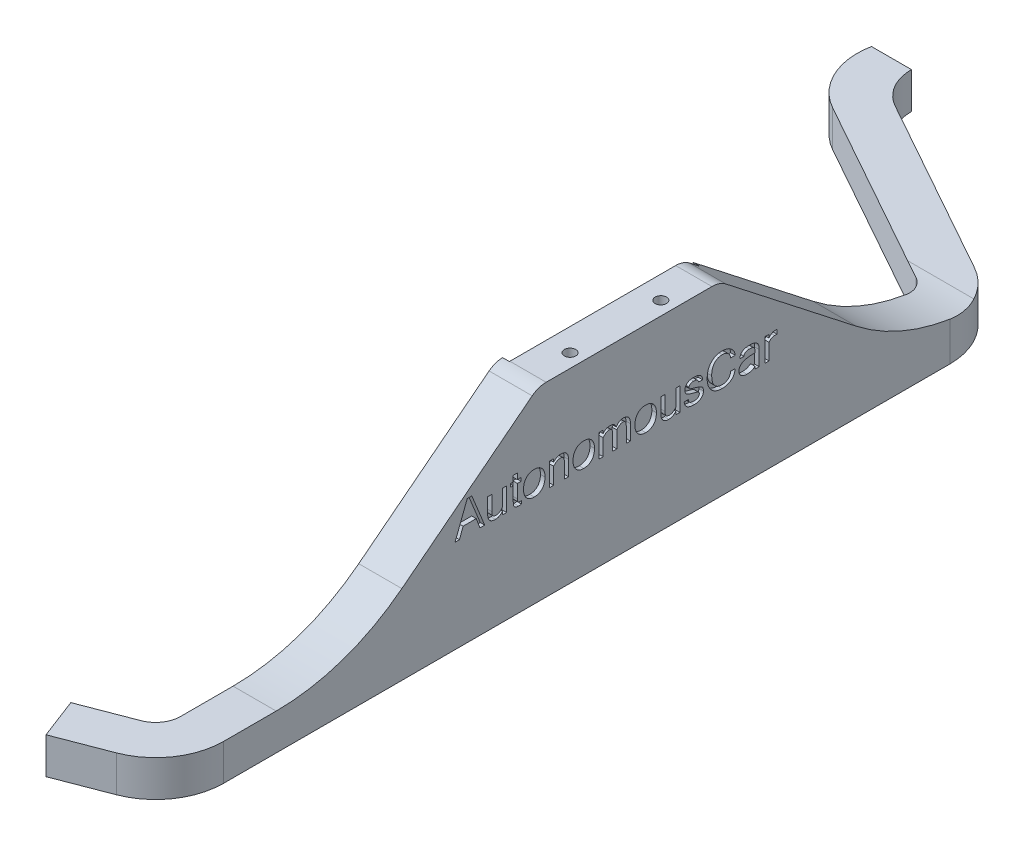
SolidWorks part; units mm, degrees
ref_plane "Plan de face" through (0, 0, 0) normal (0, 0, 1) x (1, 0, 0)
ref_plane "Plan de dessus" through (0, 0, 0) normal (0, 1, 0) x (1, 0, 0)
ref_plane "Plan de droite" through (0, 0, 0) normal (1, 0, 0) x (0, 0, -1)
sketch "Esquisse1" plane through (0, 0, 0) normal (0, 1, 0) x (1, 0, 0)
  line L0 (50.7636, -98.741) -> (61.9667, -94.4409)
  line L1 (65.5, -89.3) -> (65.5, 70.7)
  line L2 (62.6824, 75.5015) -> (21.1873, 98.6833)
  line L3 (54.1678, -107.6101) -> (50.7636, -98.741)
  line L4 (67.3157, 83.795) -> (27.7151, 105.9185)
  line L5 (75, -89.3) -> (75, 70.7)
  line L6 (13.7802, 114.6485) -> (22.5922, 114.6485)
  line L7 (54.1678, -107.6101) -> (65.3709, -103.31)
  line L8 (27.6229, 105.97) -> (67.3157, 83.795) construction
  line L9 (11.8444, -113.6793) -> (61.9667, -94.4409) construction
  line L10 (15.2486, -122.5484) -> (65.3709, -103.31) construction
  arc A0 (61.9667, -94.4409) -> (65.5, -89.3) centre (59.9934, -89.3) ccw
  arc A1 (65.5, 70.7) -> (62.6824, 75.5015) centre (60, 70.7) ccw
  arc A2 (21.1873, 98.6833) -> (13.7802, 114.6485) centre (28.503, 111.7784) cw
  arc A3 (75, 70.7) -> (67.3157, 83.795) centre (60, 70.7) ccw construction
  arc A4 (75, 70.7) -> (67.3157, 83.795) centre (60, 70.7) ccw
  arc A5 (65.3709, -103.31) -> (75, -89.3) centre (59.9934, -89.3) ccw
  arc A6 (65.3709, -103.31) -> (75, -89.3) centre (59.9934, -89.3) ccw construction
  arc A7 (22.2903, 125.7447) -> (21.1873, 98.6833) centre (37.3736, 111.5768) ccw construction
  arc A8 (29.2146, 119.2406) -> (27.7151, 105.9185) centre (37.3736, 111.5768) ccw construction
  arc A9 (22.5922, 114.6485) -> (27.7151, 105.9185) centre (32.5922, 114.6485) ccw
  point P8 (63.2208, 78.557)
  dimension "D2" = 12
  dimension "D3" = 15
  dimension "D5" = 20
  dimension "D6" = 17
  dimension "D7" = 14.01
  dimension "D8" = 160
  dimension "D1" = 9.5
extrude "Boss.-Extru.2" add sketch "Esquisse1" along normal blind 41
sketch "Esquisse2" plane through (75, 0, 0) normal (1, 0, 0) x (0, 0, -1)
  line L0 (-107.6101, 8) -> (-77.73, 8)
  line L1 (-107.6101, 41) -> (-107.6101, 0) construction
  line L2 (-21.3226, 39.9416) -> (-50.0428, 17.5258)
  line L3 (-89.3, 41) -> (70.7, 41) construction
  line L4 (-107.6101, 8) -> (-107.6101, 51.492)
  line L6 (-107.6101, 51.492) -> (114.6485, 51.492)
  line L7 (114.6485, 51.492) -> (114.6485, 8)
  line L8 (114.6485, 41) -> (114.6485, 0) construction
  line L9 (114.6485, 8) -> (77.7635, 8)
  line L10 (21.3561, 39.9416) -> (50.0763, 17.5258)
  line L11 (-18.2462, 41) -> (18.2797, 41)
  line L12 (83.795, 0) -> (105.9185, 0) construction
  arc A0 (-21.3226, 39.9416) -> (-18.2462, 41) centre (-18.2462, 36) cw
  arc A1 (21.3561, 39.9416) -> (18.2797, 41) centre (18.2797, 36) ccw
  arc A2 (50.0763, 17.5258) -> (77.7635, 8) centre (77.7635, 53) ccw
  arc A3 (-77.73, 8) -> (-50.0428, 17.5258) centre (-77.73, 53) ccw
  point P18 (-19.9665, 41)
  point P21 (20, 41)
  dimension "D1" = 5
  dimension "D2" = 45
  dimension "D3" = 8
extrude "Enlèv. mat.-Extru.1" cut sketch "Esquisse2" against normal up to next
sketch "Esquisse3" plane through (0, 0, 0) normal (0, -1, 0) x (1, 0, 0)
  line L0 (26.6422, -101.0785) -> (64.9998, -79.6495) construction
  line L1 (67.3157, -83.795) -> (27.7151, -105.9185) construction
  line L2 (50.7636, 98.741) -> (54.1678, 107.6101) construction
  line L3 (54.1678, 107.6101) -> (65.3709, 103.31) construction
  line L4 (70.25, 89.3001) -> (70.2514, -70.6999) construction
  line L5 (72, 89.3001) -> (72, -70.6999) construction
  line L6 (75, 89.3) -> (75, -70.7) construction
  line L7 (22.5922, -114.6485) -> (13.7802, -114.6485) construction
  line L19 (52.4657, 103.1755) -> (63.6688, 98.8754) construction
  circle A0 centre (72, 11.0015) radius 1.25
  arc A1 (75, 89.3) -> (65.3709, 103.31) centre (59.9934, 89.3) ccw construction
  arc A2 (64.9998, -79.6495) -> (70.2514, -70.6999) centre (60, -70.7) ccw construction
  arc A3 (67.3157, -83.795) -> (75, -70.7) centre (60, -70.7) ccw construction
  circle A4 centre (72, -39.0785) radius 1.25
  circle A5 centre (63.03, 98.9215) radius 1.25
  circle A8 centre (65.8488, -79.1752) radius 1.25
  arc A12 (70.25, 89.3001) -> (63.6688, 98.8754) centre (59.9934, 89.3) ccw construction
  circle A13 centre (26.6422, -101.0785) radius 1.25
  circle A15 centre (72, 61.0815) radius 1.25
  point P18 (0, 0)
  point P30 (63.03, 98.3418)
  point P36 (63.0154, 97.8707)
  dimension "D2" = 2.5
  dimension "D3" = 4.05
  dimension "D1" = 13.57
  dimension "D4" = 44.91
  dimension "D5" = 3
  dimension "D6" = 75.57
  dimension "D7" = 50.08
  dimension "D8" = 50.08
  dimension "D9" = 8.97
  dimension "D10" = 37.84
extrude "Enlèv. mat.-Extru.2" cut sketch "Esquisse3" against normal blind 5
sketch "Esquisse5" plane through (0, 0, 0) normal (0, -1, 0) x (1, 0, 0)
  line L0 (65.5, -70.7) -> (65.5, 89.3) construction
  line L1 (65.5, 18.3515) -> (67, 18.3515)
  line L2 (65.5, 18.3515) -> (65.5, -23.6485)
  line L3 (65.5, -23.6485) -> (67, -23.6485)
  line L4 (67, 18.3515) -> (67, -23.6485)
  line L5 (22.5922, -114.6485) -> (13.7802, -114.6485) construction
  dimension "D1" = 42
  dimension "D2" = 91
  dimension "D3" = 1.5
extrude "Enlèv. mat.-Extru.4" cut sketch "Esquisse5" against normal up to surface (41 mm away) up to face at (70.25, 41, -0.0168)
sketch "Esquisse4" plane through (0, 41, 0) normal (0, 1, 0) x (1, 0, 0)
  line L1 (72, 18.2797) -> (72, -18.2462) construction
  line L5 (67, 0.0168) -> (75, 0.0168) construction
  line L6 (67, 18.2797) -> (67, -18.2462) construction
  line L7 (75, -18.2462) -> (75, 18.2797) construction
  line L8 (67, -18.2462) -> (75, -18.2462) construction
  line L9 (67, 18.2797) -> (75, 18.2797) construction
  circle A0 centre (72, 10.0168) radius 1.25
  circle A1 centre (72, -9.9832) radius 1.25
  point P2 (72, -9.8451)
  point P3 (72, -18.2462)
  point P17 (71, 9.1145)
  point P18 (71, -8.9883)
  point P19 (72, 18.2797)
  point P22 (72, -10.7256)
  dimension "D1" = 2.5
  dimension "D2" = 3
  dimension "D3" = 20
  dimension "D4" = 10
extrude "Enlèv. mat.-Extru.3" cut sketch "Esquisse4" against normal blind 5
sketch "Esquisse6" plane through (75, 0, 0) normal (1, 0, 0) x (0, 0, -1)
  line L0 (0, 0) -> (0.0168, 41) construction
  line L1 (-18.2462, 41) -> (18.2797, 41) construction
  line L2 (-46.2321, 20.5) -> (46.2656, 20.5) construction
  line L3 (-50.0428, 17.5258) -> (-21.3226, 39.9416) construction
  line L4 (21.3561, 39.9416) -> (50.0763, 17.5258) construction
  point P11 (0.0084, 20.5)
sketch "Esquisse7" plane through (75, 0, 0) normal (1, 0, 0) x (0, 0, -1)
  text T0 "   AutonomousCar" font "Microsoft Sans Serif" height 7
extrude "Enlèv. mat.-Extru.5" cut sketch "Esquisse7" against normal blind 1
sketch "Esquisse8" plane through (75, 0, 0) normal (1, 0, 0) x (0, 0, -1)
  line L0 (-36.2946, 23.4091) -> (-33.931, 23.4091)
  line L1 (-33.931, 23.4091) -> (-35.144, 26.6065)
  line L2 (-35.144, 26.6065) -> (-36.2946, 23.4091)
  ellipse E0 centre (-20.8685, 23.0455) end of major axis (-18.8685, 23.0455) minor radius 1.9091
  ellipse E1 centre (-9.9594, 23.0455) end of major axis (-11.9594, 23.0455) minor radius 1.9091
  ellipse E2 centre (3.677, 23.0455) end of major axis (5.677, 23.0455) minor radius 1.9091
  ellipse E3 centre (26.5135, 22.0458) end of major axis (28.426, 22.7768) minor radius 1.2468
  spline S0 degree 3 poles (-20.8685, 21.1364) (-20.8158, 21.1376) (-20.7124, 21.1399) (-20.5609, 21.1633) (-20.4171, 21.2015) (-20.281, 21.2547) (-20.1521, 21.3213) (-20.0318, 21.4049) (-19.9197, 21.5037) (-19.8139, 21.616) (-19.7184, 21.7435) (-19.6378, 21.8875) (-19.5678, 22.0442) (-19.5111, 22.216) (-19.4674, 22.4024) (-19.4372, 22.6034) (-19.4161, 22.8182) (-19.4147, 22.9663) (-19.4139, 23.0426) knots 0 0 0 0 0.058302 0.114552 0.16941 0.222905 0.276181 0.329743 0.384781 0.441578 0.500452 0.560849 0.624035 0.690407 0.761043 0.835923 0.915495 1 1 1 1 construction
  spline S1 degree 3 poles (3.677, 24.9545) (3.6244, 24.9533) (3.5209, 24.9509) (3.3694, 24.9278) (3.226, 24.8888) (3.0888, 24.8383) (2.9611, 24.7692) (2.8403, 24.6862) (2.7282, 24.5872) (2.6224, 24.4749) (2.5269, 24.3474) (2.4464, 24.2034) (2.376, 24.0463) (2.3199, 23.8738) (2.2757, 23.6866) (2.2458, 23.4847) (2.2246, 23.2684) (2.2232, 23.1194) (2.2225, 23.0426) knots 0 0 0 0 0.058179 0.11431 0.169051 0.222245 0.275653 0.329102 0.384023 0.440701 0.49945 0.559719 0.622771 0.6895 0.759986 0.835225 0.91515 1 1 1 1 construction
  spline S2 degree 3 poles (5.1315, 23.0426) (5.1308, 23.1194) (5.1294, 23.2684) (5.1082, 23.4847) (5.0783, 23.6866) (5.0341, 23.8738) (4.978, 24.0463) (4.9076, 24.2034) (4.8271, 24.3474) (4.7316, 24.4749) (4.6258, 24.5872) (4.5137, 24.6862) (4.3929, 24.7692) (4.2652, 24.8383) (4.128, 24.8888) (3.9846, 24.9278) (3.8331, 24.9509) (3.7296, 24.9533) (3.677, 24.9545) knots 0 0 0 0 0.08485 0.164775 0.240014 0.3105 0.377229 0.440281 0.50055 0.559299 0.615977 0.670898 0.724347 0.777755 0.830949 0.88569 0.941821 1 1 1 1 construction
  point P7 (26.6088, 22.1298)
  point P37 (25.1315, 21.9176)
  point P40 (25.7583, 21.0203)
  point P46 (28.4248, 22.2323)
  point P48 (25.9261, 20.927)
  point P49 (24.8073, 21.2067)
  point P50 (26.2897, 20.694)
  point P51 (26.2897, 22.9595)
  point P52 (28.201, 22.1204)
  point P53 (26.5135, 22.0458)
  dimension "D1" = 4
  dimension "D2" = 4
  dimension "D3" = 4
extrude "Enlèv. mat.-Extru.6" cut sketch "Esquisse8" against normal up to surface (1 mm away) up to face at (74, 24.4749, 35.1232)
